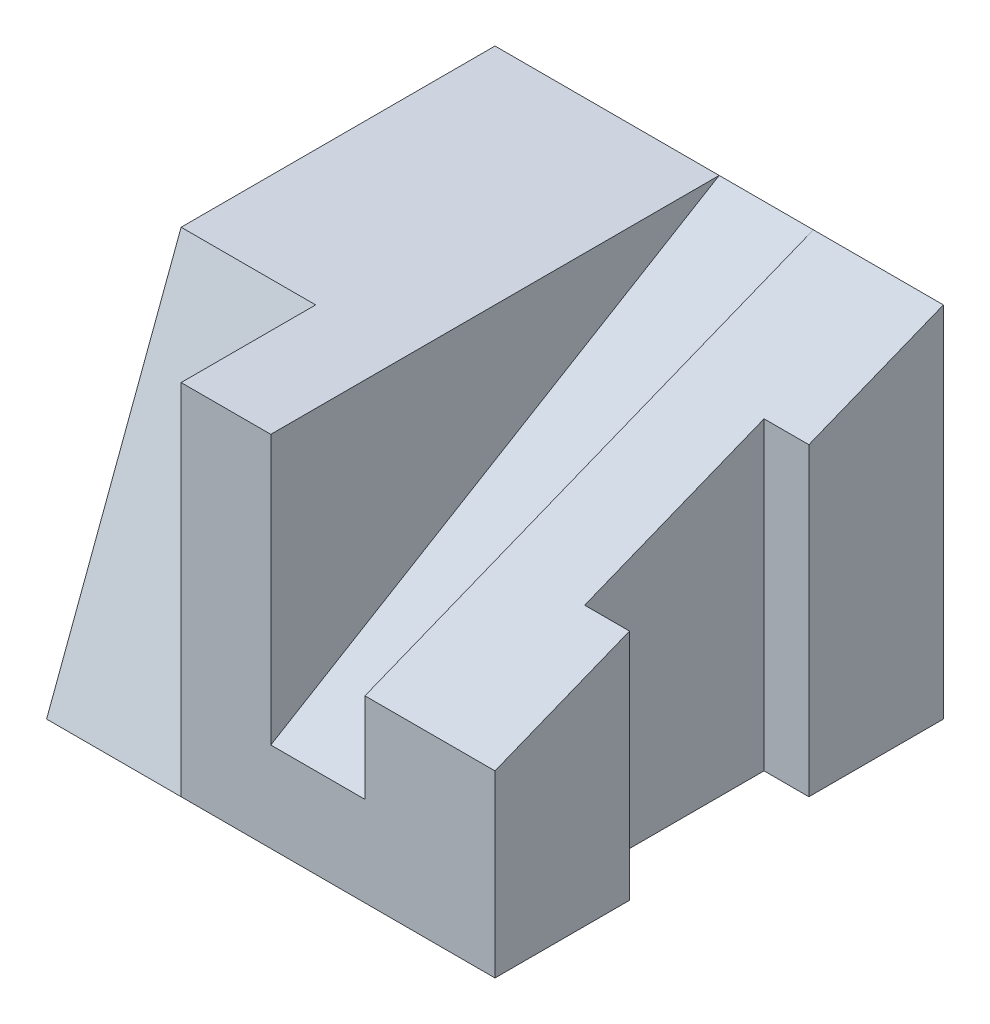
SolidWorks part; units mm, degrees
ref_plane "Front Plane" through (0, 0, 0) normal (0, 0, 1) x (1, 0, 0)
ref_plane "Top Plane" through (0, 0, 0) normal (0, 1, 0) x (1, 0, 0)
ref_plane "Right Plane" through (0, 0, 0) normal (1, 0, 0) x (0, 0, -1)
sketch "Sketch1" plane through (0, 0, 0) normal (0, 0, 1) x (1, 0, 0)
  line L1 (0, 0) -> (100, 0)
  line L2 (0, 0) -> (0, 80)
  line L3 (0, 80) -> (100, 80)
  line L4 (100, 0) -> (100, 80)
  dimension "D1" = 80
  dimension "D2" = 100
extrude "Boss-Extrude1" add sketch "Sketch1" against normal blind 100
sketch "Sketch3" plane through (0, 0, 0) normal (-1, 0, 0) x (0, 0, 1)
  line L0 (0, 0) -> (-30, 80)
  line L1 (-100, 80) -> (0, 80) construction
  line L2 (-30, 80) -> (0, 80)
  line L3 (0, 80) -> (0, 0)
  dimension "D1" = 30
extrude "Cut-Extrude1" cut sketch "Sketch3" against normal blind 30
sketch "Sketch5" plane through (100, 0, 0) normal (1, 0, 0) x (0, 0, -1)
  line L0 (0, 40) -> (100, 80)
  line L1 (0, 0) -> (0, 80) construction
  line L2 (100, 80) -> (0, 80)
  line L3 (0, 80) -> (0, 40)
  dimension "D1" = 40
extrude "Cut-Extrude2" cut sketch "Sketch5" against normal blind 50
sketch "Sketch8" plane through (100, 0, 0) normal (1, 0, 0) x (0, 0, -1)
  line L0 (0, 20) -> (100, 80)
  line L1 (0, 0) -> (0, 40) construction
  line L2 (100, 80) -> (0, 40)
  line L3 (0, 40) -> (0, 20)
  dimension "D1" = 20
extrude "Cut-Extrude4" cut sketch "Sketch8" against normal blind 20 and the other way blind 1 from offset 30 offset against normal yes
sketch "Sketch7" plane through (100, 0, 0) normal (1, 0, 0) x (0, 0, -1)
  line L0 (30, 52) -> (30, 0)
  line L1 (0, 40) -> (100, 80) construction
  line L2 (100, 0) -> (0, 0) construction
  line L3 (30, 0) -> (70, 0)
  line L4 (70, 0) -> (70, 68)
  line L5 (70, 68) -> (30, 52)
  dimension "D1" = 40
  dimension "D2" = 30
extrude "Cut-Extrude3" cut sketch "Sketch7" against normal blind 10
